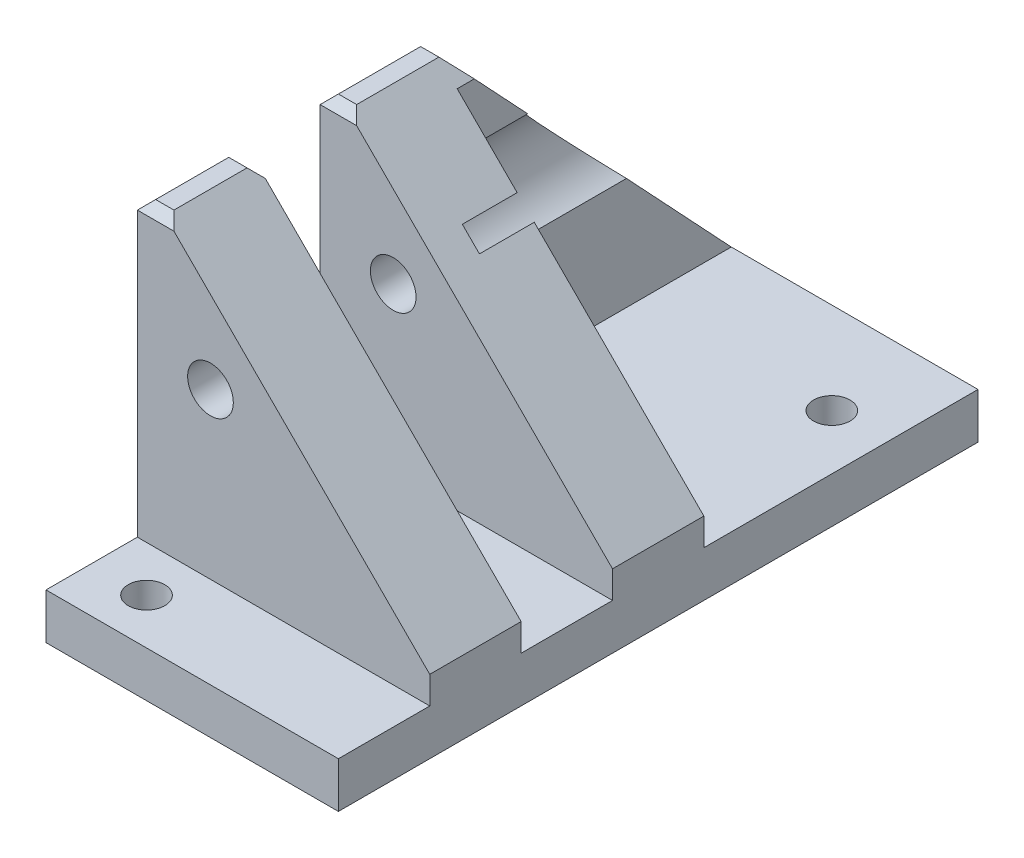
SolidWorks part; units mm, degrees
ref_plane "前视基准面" through (0, 0, 0) normal (0, 0, 1) x (1, 0, 0)
ref_plane "上视基准面" through (0, 0, 0) normal (0, 1, 0) x (1, 0, 0)
ref_plane "右视基准面" through (0, 0, 0) normal (1, 0, 0) x (0, 0, -1)
sketch "草图1" plane through (0, 0, 0) normal (0, 0, 1) x (1, 0, 0)
  line L0 (0, 0) -> (50, 0)
  line L1 (50, 0) -> (0, 50)
  line L2 (0, 50) -> (0, 0)
  dimension "D1" = 50
extrude "拉伸1" add sketch "草图1" along normal blind 70
sketch "草图2" plane through (0, 0, 70) normal (0, 0, 1) x (1, 0, 0)
  line L0 (50, 0) -> (32, 0)
  line L1 (0, 0) -> (50, 0) construction
  line L2 (32, 0) -> (32, 18)
  line L3 (50, 0) -> (0, 50) construction
  line L4 (32, 18) -> (50, 0)
  line L5 (0, 50) -> (0, 0) construction
  dimension "D1" = 32
extrude "切除-拉伸1" cut sketch "草图2" against normal through all
sketch "草图3" plane through (32, 0, 0) normal (1, 0, 0) x (0, 0, -1)
  line L0 (-70, 50) -> (0, 50) construction
  line L1 (-70, 50) -> (-60, 50)
  line L2 (-70, 50) -> (-70, 5)
  line L3 (-70, 5) -> (-60, 5)
  line L4 (-60, 50) -> (-60, 5)
  line L5 (-50, 50) -> (-40, 50)
  line L6 (-50, 50) -> (-50, 5)
  line L7 (-50, 5) -> (-40, 5)
  line L8 (-40, 50) -> (-40, 5)
  line L9 (0, 0) -> (-70, 0) construction
  dimension "D1" = 10
  dimension "D2" = 10
  dimension "D3" = 10
  dimension "D4" = 5
extrude "切除-拉伸2" cut sketch "草图3" against normal through all
sketch "草图6" plane through (0, 0, 70) normal (0, 0, 1) x (1, 0, 0)
  line L0 (0, 50) -> (0, 40)
  line L2 (0, 40) -> (32, 8)
  line L4 (32, 8) -> (32, 18)
  line L5 (32, 18) -> (0, 50)
  line L6 (0, 0) -> (32, 0) construction
  dimension "D1" = 40
extrude "切除-拉伸5" cut sketch "草图6" against normal through all
sketch "草图7" plane through (0, 0, 70) normal (0, 0, 1) x (1, 0, 0)
  line L0 (0, 40) -> (0, 37)
  line L2 (0, 37) -> (3, 37)
  line L4 (3, 37) -> (0, 40)
  dimension "D1" = 3
extrude "切除-拉伸6" cut sketch "草图7" against normal through all
sketch "草图8" plane through (32, 0, 0) normal (1, 0, 0) x (0, 0, -1)
  line L0 (0, 0) -> (-70, 0) construction
  line L1 (-30, 5) -> (0, 5)
  line L2 (-30, 5) -> (-30, 37)
  line L3 (-30, 37) -> (0, 37)
  line L4 (0, 5) -> (0, 37)
  line L5 (-40, 8) -> (-40, 37) construction
  dimension "D1" = 5
  dimension "D2" = 10
extrude "切除-拉伸7" cut sketch "草图8" against normal blind 27
sketch "草图9" plane through (5, 0, 0) normal (1, 0, 0) x (0, 0, -1)
  line L0 (0, 5) -> (0, 37)
  line L1 (0, 37) -> (-30, 37)
  line L3 (-30, 37) -> (0, 5)
  line L4 (0, 37) -> (-40, 37) construction
  line L5 (-30, 35) -> (-30, 41.4407) construction
extrude "切除-拉伸8" cut sketch "草图9" against normal through all
sketch "草图10" plane through (0, 0, 0) normal (0, -1, 0) x (1, 0, 0)
  line L0 (0, 70) -> (32, 70) construction
  line L1 (0, 70) -> (0, 0) construction
  line L2 (0, 0) -> (32, 0) construction
  line L3 (32, 0) -> (32, 70) construction
  circle A0 centre (6, 65) radius 2
  circle A1 centre (26, 10) radius 2
  dimension "D1" = 4
  dimension "D2" = 5
  dimension "D3" = 6
  dimension "D4" = 10
  dimension "D5" = 6
extrude "切除-拉伸9" cut sketch "草图10" against normal blind 27
sketch "草图15" plane through (0, 0, 70) normal (0, 0, 1) x (1, 0, 0)
  line L0 (0, 5) -> (0, 0) construction
  line L1 (0, 0) -> (32, 0) construction
  circle A0 centre (8, 23) radius 2.5
  dimension "D3" = 5
  dimension "D1" = 8
  dimension "D2" = 23
extrude "切除-拉伸11" cut sketch "草图15" against normal through all
sketch "草图16" plane through (0, 0, 30) normal (0, 0, -1) x (-1, 0, 0)
  circle A0 centre (-8, 23) radius 6.5
  dimension "D1" = 13
extrude "切除-拉伸12" cut sketch "草图16" against normal blind 6 and the other way blind 26
chamfer "倒角1" distance 1 angle 45 5 edges at (1.5, 37, 40) (0, 37, 35) (1.5, 37, 50) (1.5, 37, 60) (0, 37, 55)
